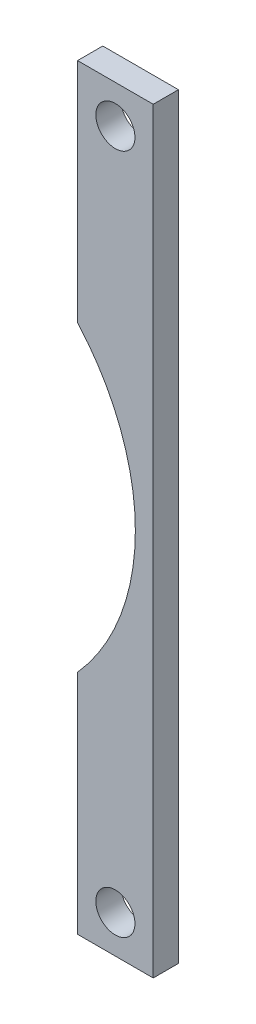
SolidWorks part; units mm, degrees
material "5052-O"
ref_plane "正面" through (0, 0, 0) normal (0, 0, 1) x (1, 0, 0)
ref_plane "平面" through (0, 0, 0) normal (0, 1, 0) x (1, 0, 0)
ref_plane "右側面" through (0, 0, 0) normal (1, 0, 0) x (0, 0, -1)
sketch "ｽｹｯﾁ1" plane through (0, 0, 0) normal (0, 0, 1) x (1, 0, 0)
  line L1 (3, -30) -> (-3, -30)
  line L2 (3, -30) -> (3, 30)
  line L3 (3, 30) -> (-3, 30)
  line L4 (-3, -30) -> (-3, 30)
  line L5 (3, -30) -> (-3, 30) construction
  line L6 (3, 30) -> (-3, -30) construction
  circle A0 centre (0, 27) radius 1.55
  circle A1 centre (0, -27) radius 1.55
  point P0 (0, 0)
  dimension "D1" = 3
  dimension "D2" = 3
  dimension "D4" = 3
  dimension "D5" = 3
  dimension "D6" = 3.1
  dimension "D3" = 6
  dimension "D7" = 60
extrude "ﾎﾞｽ - 押し出し1" add sketch "ｽｹｯﾁ1" along normal blind 2
sketch "ｽｹｯﾁ2" plane through (0, 0, 2) normal (0, 0, 1) x (1, 0, 0)
  line L0 (-3, 30) -> (-3, -30) construction
  line L1 (-3, 12) -> (-3, -12)
  line L2 (-16.4164, 0) -> (0, 0) construction
  arc A0 (-3, 12) -> (-3, -12) centre (-16.4164, 0) cw
  dimension "D2" = 18
  dimension "D1" = 24
extrude "ｶｯﾄ - 押し出し1" cut sketch "ｽｹｯﾁ2" against normal through all
